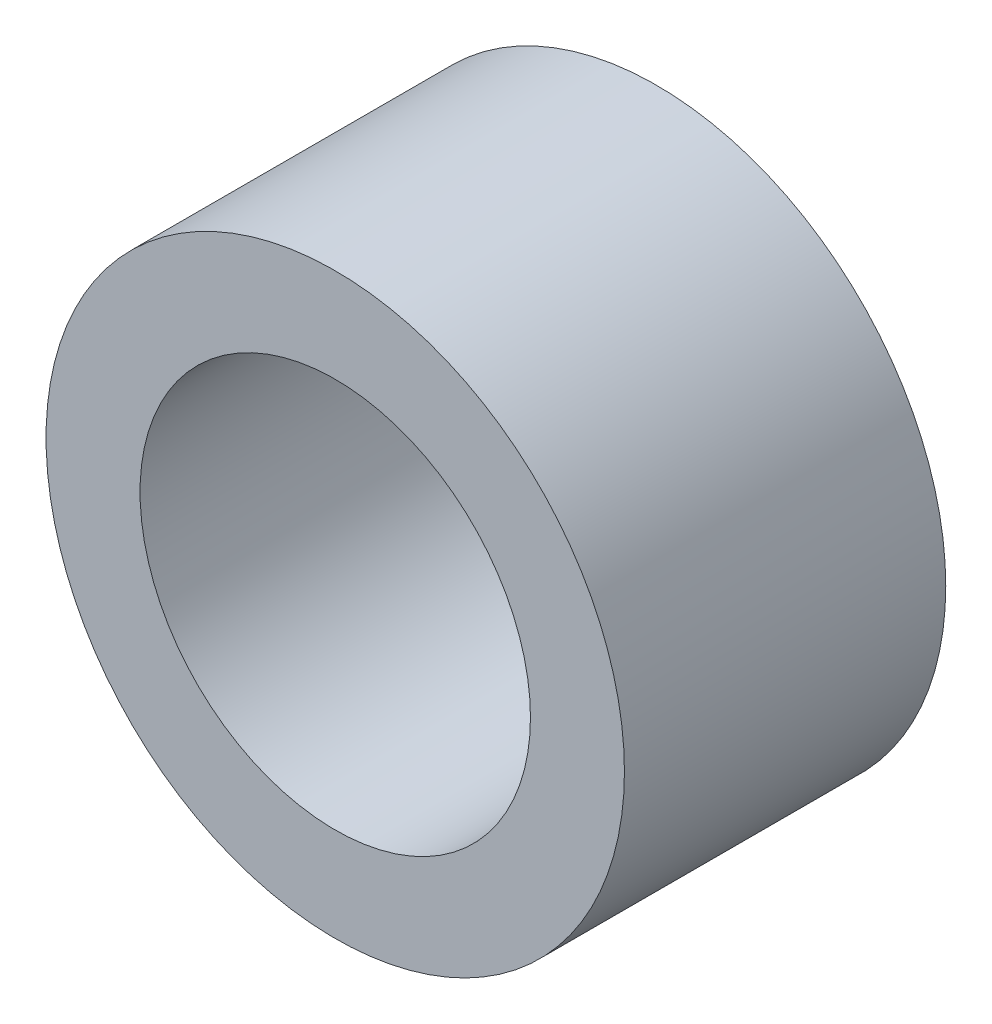
SolidWorks part; units mm, degrees
ref_plane "前视基准面" through (0, 0, 0) normal (0, 0, 1) x (1, 0, 0)
ref_plane "上视基准面" through (0, 0, 0) normal (0, 1, 0) x (1, 0, 0)
ref_plane "右视基准面" through (0, 0, 0) normal (1, 0, 0) x (0, 0, -1)
other "Configuration Table"
sketch "草图1" plane through (0, 0, 0) normal (0, 0, 1) x (1, 0, 0)
  circle A0 centre (0, 0) radius 36
  circle A1 centre (0, 0) radius 24.3
  dimension "D1" = 72
  dimension "D2" = 48.6
extrude "凸台-拉伸1" add sketch "草图1" along normal blind 40
